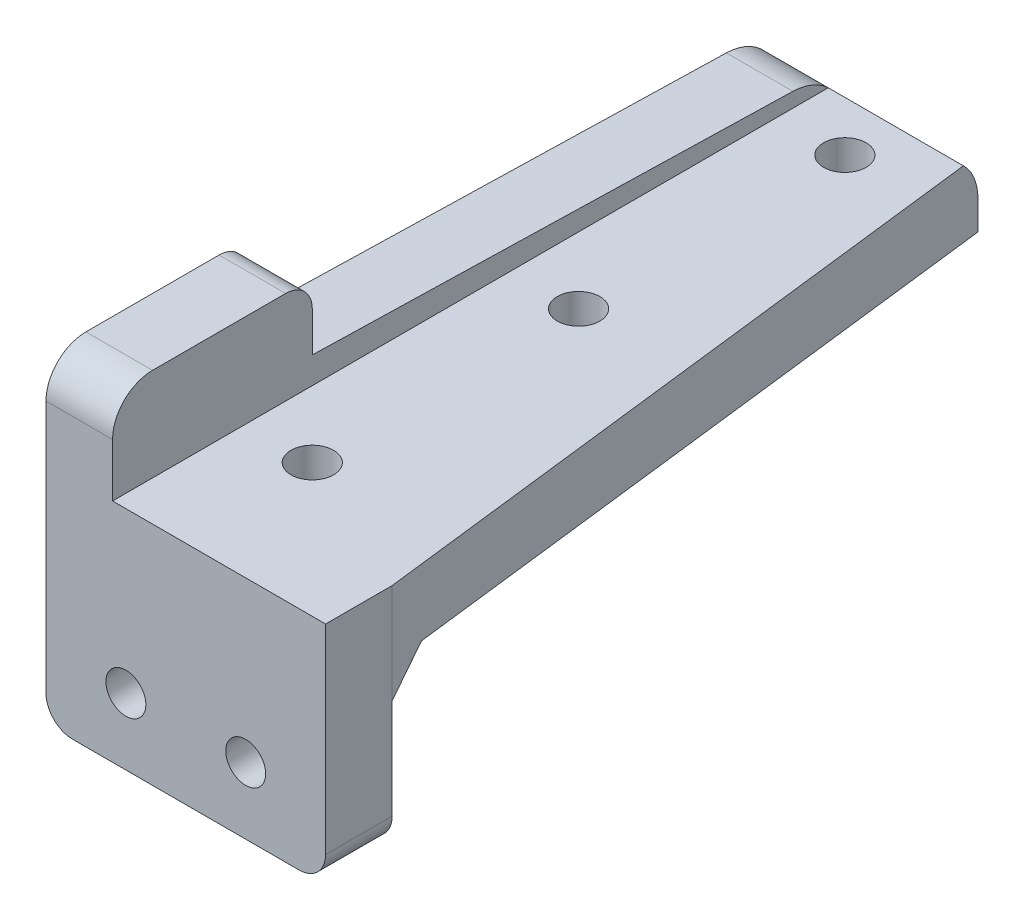
SolidWorks part; units mm, degrees
material "聚脂树脂"
ref_plane "前视基准面" through (0, 0, 0) normal (0, 0, 1) x (1, 0, 0)
ref_plane "上视基准面" through (0, 0, 0) normal (0, 1, 0) x (1, 0, 0)
ref_plane "右视基准面" through (0, 0, 0) normal (1, 0, 0) x (0, 0, -1)
other "Configuration Table"
sketch "草图1" plane through (0, 0, 0) normal (0, 1, 0) x (1, 0, 0)
  line L0 (7.5, 25) -> (13.5, -25)
  line L1 (-7.5, -25) -> (7.5, -25)
  line L2 (-7.5, -25) -> (-7.5, 25)
  line L3 (-7.5, 25) -> (7.5, 25)
  line L4 (7.5, -25) -> (7.5, 25)
  line L5 (-7.5, -25) -> (7.5, 25) construction
  line L6 (-7.5, 25) -> (7.5, -25) construction
  line L7 (13.5, -25) -> (7.5, -25)
  point P0 (0, 0)
  dimension "D1" = 15
  dimension "D2" = 50
  dimension "D3" = 6
extrude "凸台-拉伸1" add sketch "草图1" along normal blind 5 contours L1 L4 L3 L2 | L7 L0 L4
sketch "草图4" plane through (-7.5, 0, 0) normal (-1, 0, 0) x (0, 0, 1)
  line L0 (-25, 5) -> (25, 5)
  line L1 (25, 5) -> (25, 6)
  line L2 (25, 6) -> (-25, 6)
  line L3 (-25, 6) -> (-25, 5)
  line L4 (-25, 6) -> (15, 7)
  line L5 (25, 7) -> (25, 6)
  line L6 (15, 7) -> (25, 7)
  line L7 (15, 7) -> (15, 12)
  line L8 (15, 12) -> (25, 12)
  line L9 (25, 12) -> (25, 7)
  dimension "D1" = 1
  dimension "D2" = 1
  dimension "D3" = 10
  dimension "D4" = 5
extrude "凸台-拉伸2" add sketch "草图4" against normal blind 5
fillet "圆角1" radius 4 1 edges at (-5, 6, -25)
fillet "圆角3" radius 2 1 edges at (-5, 12, 15)
sketch "草图5" plane through (0, 5, 0) normal (0, 1, 0) x (1, 0, 0)
  line L0 (-2.5, -25) -> (-2.5, 23.7537) construction
  line L1 (-2.5, 21.1) -> (-2.5, -15) construction
  line L2 (-7.5, 25) -> (7.5, 25) construction
  circle A0 centre (2.5, 20) radius 1.6
  circle A1 centre (2.5, 0) radius 1.6
  circle A2 centre (2.5, -20) radius 1.6
  dimension "D1" = 3.2
  dimension "D2" = 3.2
  dimension "D3" = 3.2
  dimension "D4" = 5
  dimension "D5" = 5
  dimension "D6" = 5
  dimension "D7" = 20
  dimension "D8" = 20
  dimension "D9" = 5
extrude "切除-拉伸1" cut sketch "草图5" against normal blind 5
sketch "草图7" plane through (0, 0, 25) normal (0, 0, 1) x (1, 0, 0)
  line L0 (13.5, 0) -> (13.5, 5)
  line L1 (13.5, 5) -> (-2.5, 5)
  line L2 (-2.5, 5) -> (-2.5, 12)
  line L3 (-2.5, 12) -> (-7.5, 12)
  line L4 (-7.5, 12) -> (-7.5, 0)
  line L5 (-7.5, 0) -> (-7.5, -12)
  line L6 (-7.5, -12) -> (13.5, -12)
  line L7 (13.5, -12) -> (13.5, 0)
  circle A0 centre (-1.5, -7) radius 1.5
  circle A1 centre (7.5, -7) radius 1.5
  dimension "D2" = 3
  dimension "D3" = 3
  dimension "D1" = 12
  dimension "D4" = 5
  dimension "D5" = 5
  dimension "D6" = 6
  dimension "D7" = 6
extrude "凸台-拉伸3" add sketch "草图7" along normal blind 5 contours L0 L1 L2 L3 L4 L5 L6 L7 | A0 | A1
chamfer "倒角1" distance 2.5 angle 45 1 edges at (3, 0, 25)
fillet "圆角8" radius 3 1 edges at (-5, 12, 30)
sketch "草图8" plane through (-7.5, 0, 0) normal (-1, 0, 0) x (0, 0, 1)
  line L0 (25, -12) -> (25, -2.5)
  line L1 (25, -2.5) -> (22.5, 0)
  line L2 (22.5, 0) -> (-7.5, 0)
  line L3 (22.5, 0) -> (-25, 0) construction
  line L4 (-7.5, 0) -> (25, -12)
  dimension "D1" = 30
extrude "凸台-拉伸4" add sketch "草图8" against normal blind 3
fillet "圆角9" radius 2 2 edges at (-7.5, -12, 27.5) (13.5, -12, 27.5)
